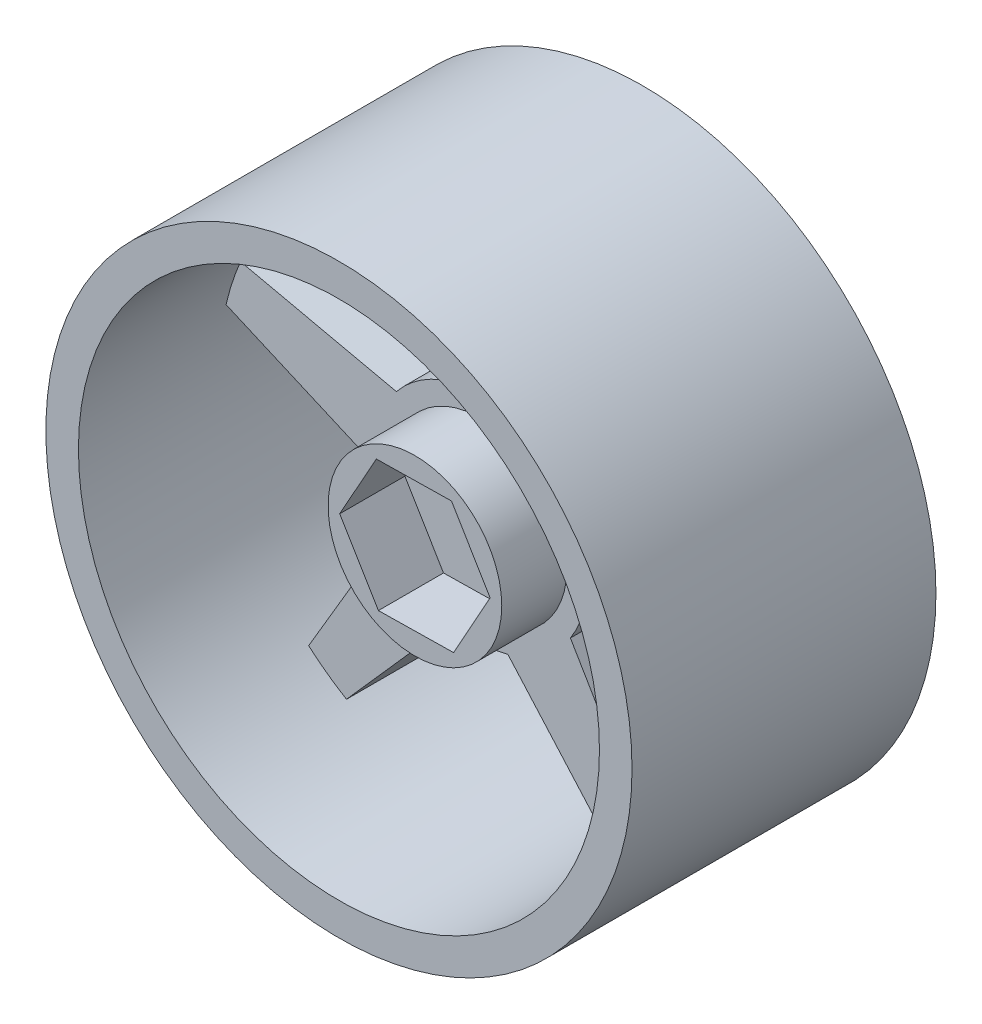
SolidWorks part; units mm, degrees
ref_plane "前视基准面" through (0, 0, 0) normal (0, 0, 1) x (1, 0, 0)
ref_plane "上视基准面" through (0, 0, 0) normal (0, 1, 0) x (1, 0, 0)
ref_plane "右视基准面" through (0, 0, 0) normal (1, 0, 0) x (0, 0, -1)
other "Configuration Table"
sketch "草图1" plane through (0, 0, 0) normal (0, 0, 1) x (1, 0, 0)
  circle A0 centre (0, 0) radius 24
  circle A1 centre (0, 0) radius 27
  dimension "D1" = 48
  dimension "D2" = 54
extrude "凸台-拉伸1" add sketch "草图1" along normal blind 28 contours A0 | A1
sketch "草图2" plane through (0, 0, 0) normal (0, 0, 1) x (1, 0, 0)
  line L0 (0, 0) -> (0, 28.4054) construction
  line L1 (-2, 25.5) -> (-3.56, 9.26)
  line L2 (-2, 25.5) -> (2, 25.5)
  line L3 (2, 25.5) -> (3.56, 9.26)
  line L4 (23.6339, 9.782) -> (7.7067, 6.2473)
  line L5 (23.6339, 9.782) -> (24.87, 5.9778)
  line L6 (24.87, 5.9778) -> (9.9069, -0.5243)
  line L7 (16.6066, -19.4544) -> (8.323, -5.399)
  line L8 (16.6066, -19.4544) -> (13.3705, -21.8055)
  line L9 (13.3705, -21.8055) -> (2.5628, -9.584)
  line L10 (-13.3705, -21.8055) -> (-2.5628, -9.584)
  line L11 (-13.3705, -21.8055) -> (-16.6066, -19.4544)
  line L12 (-16.6066, -19.4544) -> (-8.323, -5.399)
  line L13 (-24.87, 5.9778) -> (-9.9069, -0.5243)
  line L14 (-24.87, 5.9778) -> (-23.6339, 9.782)
  line L15 (-23.6339, 9.782) -> (-7.7067, 6.2473)
  arc A0 (-3.56, 9.26) -> (-7.7067, 6.2473) centre (0, 0) ccw
  arc A1 (7.7067, 6.2473) -> (3.56, 9.26) centre (0, 0) ccw
  arc A2 (-9.9069, -0.5243) -> (-8.323, -5.399) centre (0, 0) ccw
  arc A3 (-2.5628, -9.584) -> (2.5628, -9.584) centre (0, 0) ccw
  arc A4 (8.323, -5.399) -> (9.9069, -0.5243) centre (0, 0) ccw
  point P8 (0, 25.5)
  point P28 (0, 0)
  dimension "D1" = 25.5
  dimension "D2" = 2
  dimension "D3" = 16.24
  dimension "D4" = 3.56
  dimension "D5" = 5
extrude "凸台-拉伸2" add sketch "草图2" along normal blind 15
sketch "草图3" plane through (0, 0, 15) normal (0, 0, 1) x (1, 0, 0)
  line L1 (3.5608, -5.9431) -> (6.9273, 0.1122)
  line L2 (6.9273, 0.1122) -> (3.3665, 6.0553)
  line L3 (3.3665, 6.0553) -> (-3.5608, 5.9431)
  line L4 (-3.5608, 5.9431) -> (-6.9273, -0.1122)
  line L5 (-6.9273, -0.1122) -> (-3.3665, -6.0553)
  line L6 (-3.3665, -6.0553) -> (3.5608, -5.9431)
  circle A0 centre (0, 0) radius 6 construction
  circle A1 centre (0, 0) radius 8
  dimension "D1" = 12
  dimension "D2" = 16
  dimension "D3" = 16.4714
extrude "凸台-拉伸3" add sketch "草图3" along normal blind 6
sketch "草图4" plane through (0, 0, 0) normal (0, 0, -1) x (-1, 0, 0)
  circle A0 centre (0, 0) radius 17.5
  dimension "D1" = 35
extrude "凸台-拉伸4" add sketch "草图4" against normal blind 6
